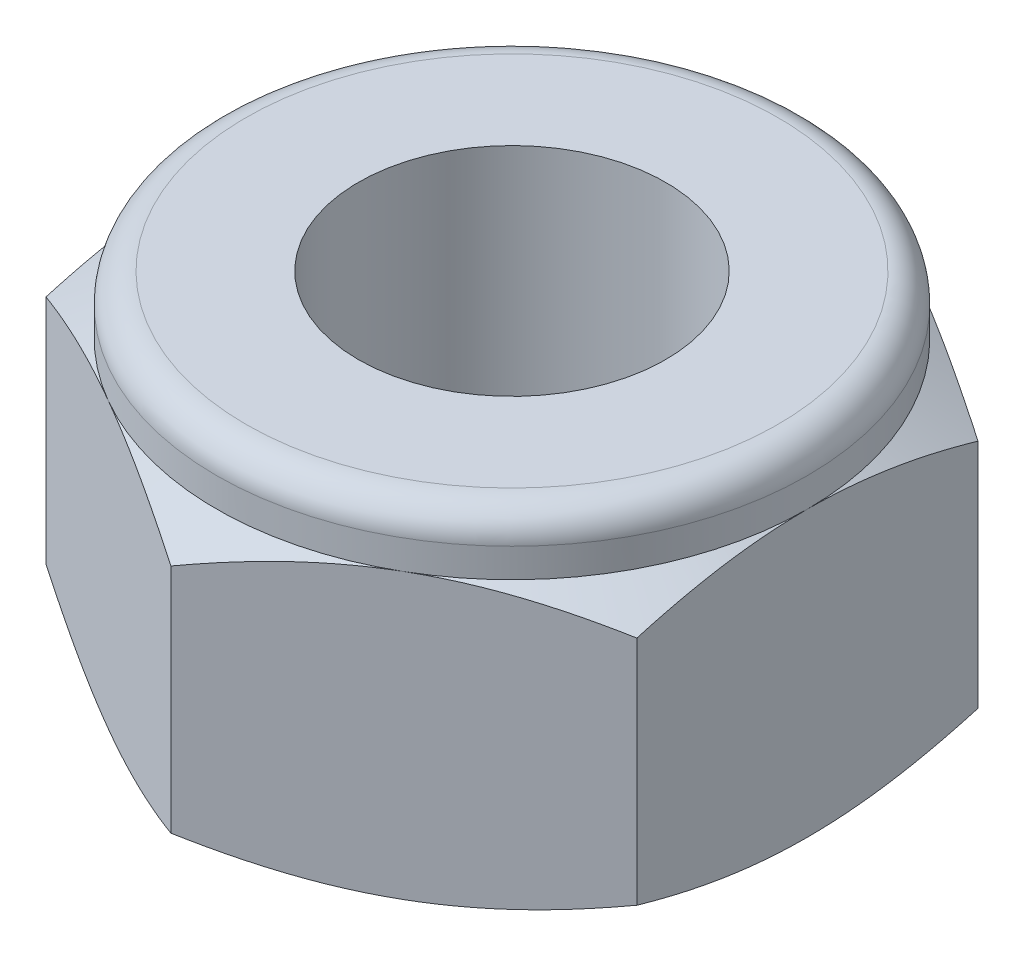
SolidWorks part; units mm, degrees
material "INOX 304: BARRA REDONDA"
ref_plane "Front Plane" through (0, 0, 0) normal (0, 0, 1) x (1, 0, 0)
ref_plane "Top Plane" through (0, 0, 0) normal (0, 1, 0) x (1, 0, 0)
ref_plane "Right Plane" through (0, 0, 0) normal (1, 0, 0) x (0, 0, -1)
sketch "Sketch1" plane through (0, 0, 0) normal (0, 1, 0) x (1, 0, 0)
  line L1 (0, -5.7735) -> (5, -2.8868)
  line L2 (5, -2.8868) -> (5, 2.8868)
  line L3 (5, 2.8868) -> (0, 5.7735)
  line L4 (0, 5.7735) -> (-5, 2.8868)
  line L5 (-5, 2.8868) -> (-5, -2.8868)
  line L6 (-5, -2.8868) -> (0, -5.7735)
  circle A0 centre (0, 0) radius 5 construction
  circle A1 centre (0, 0) radius 2.6
  dimension "D2" = 5.2
  dimension "D1" = 10
extrude "Extrude1" add sketch "Sketch1" along normal blind 5.8
sketch "Sketch2" plane through (0, 0, 0) normal (0, 0, 1) x (1, 0, 0)
  line L0 (-5, 5.8) -> (-5, 4.8094)
  line L1 (-5, 4.8094) -> (-9, 2.5)
  line L2 (-9, 2.5) -> (-9, 5.8)
  line L3 (-9, 5.8) -> (-5, 5.8)
  line L4 (0, 0) -> (0, 15.9338) construction
  line L5 (-5, 5.8) -> (-5, 0) construction
  line L6 (-5, 0) -> (0, 0) construction
  line L7 (-5, 5.8) -> (0, 5.8) construction
  line L8 (-2, 5.8) -> (0, 5.8)
  line L9 (-2, 5.8) -> (-2, 4.8)
  line L10 (-2, 4.8) -> (0, 4.8)
  line L11 (0, 5.8) -> (0, 4.8)
  line L12 (-5, 0) -> (-9, 0)
  line L13 (-9, 0) -> (-9, 2.3094)
  line L14 (-9, 2.3094) -> (-5, 0)
  dimension "D1" = 60
  dimension "D2" = 2.5
  dimension "D3" = 1
  dimension "D4" = 2
  dimension "D5" = 4
  dimension "D6" = 30
revolve "Cut-Revolve1" cut sketch "Sketch2" angle 360 about L4
fillet "Fillet1" radius 0.5 1 edges at (5, 5.8, 0)
